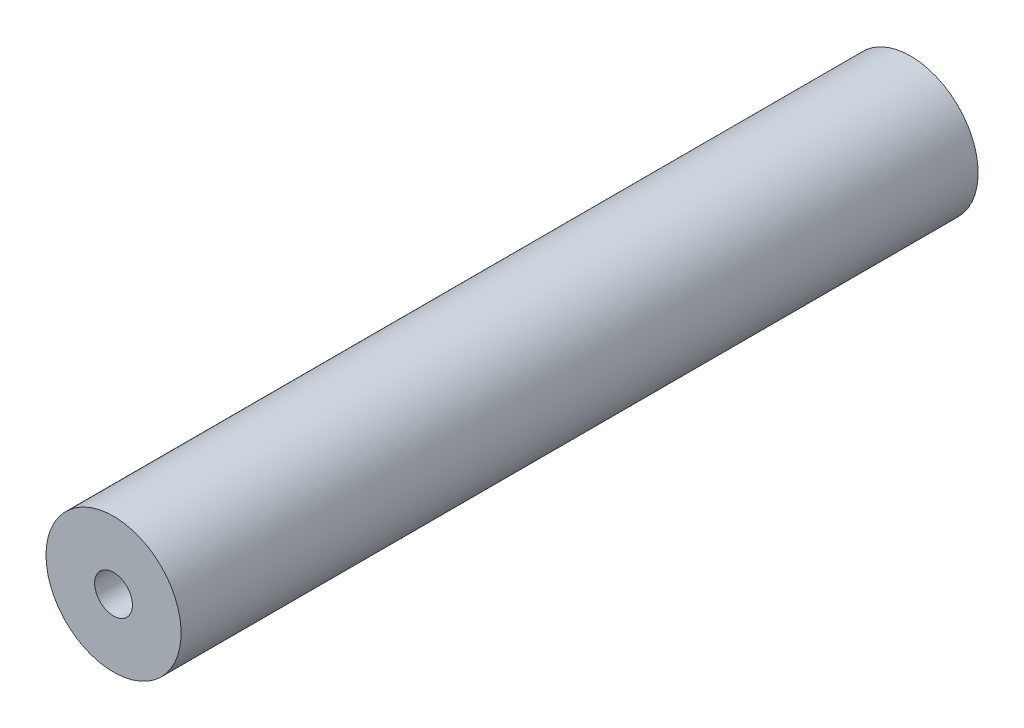
SolidWorks part; units mm, degrees
ref_plane "Front Plane" through (0, 0, 0) normal (0, 0, 1) x (1, 0, 0)
ref_plane "Top Plane" through (0, 0, 0) normal (0, 1, 0) x (1, 0, 0)
ref_plane "Right Plane" through (0, 0, 0) normal (1, 0, 0) x (0, 0, -1)
sketch "Sketch1" plane through (0, 0, 0) normal (0, 0, 1) x (1, 0, 0)
  circle A0 centre (0, 0) radius 31.75
  dimension "D1" = 63.5
extrude "Boss-Extrude1" add sketch "Sketch1" along normal blind 374.65
sketch "Sketch2" plane through (0, 0, 0) normal (0, 0, -1) x (-1, 0, 0)
  circle A0 centre (0, 0) radius 8.89
  dimension "D1" = 17.78
extrude "Cut-Extrude1" cut sketch "Sketch2" against normal through all
